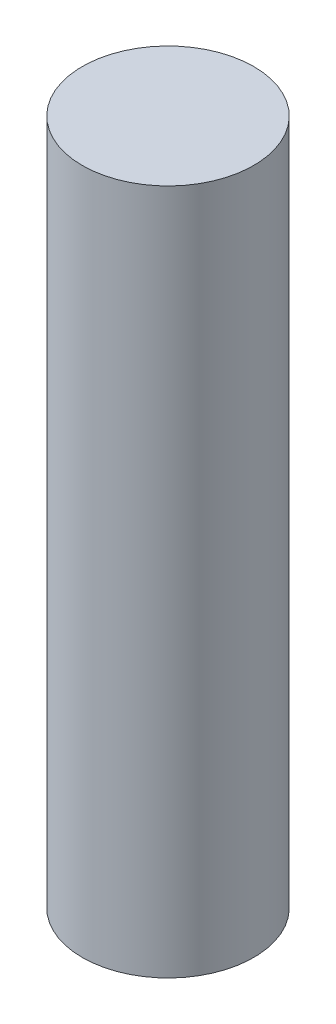
SolidWorks part; units mm, degrees
ref_plane "Front Plane" through (0, 0, 0) normal (0, 0, 1) x (1, 0, 0)
ref_plane "Top Plane" through (0, 0, 0) normal (0, 1, 0) x (1, 0, 0)
ref_plane "Right Plane" through (0, 0, 0) normal (1, 0, 0) x (0, 0, -1)
sketch "Sketch1" plane through (0, 0, 0) normal (0, 1, 0) x (1, 0, 0)
  circle A0 centre (0, 0) radius 10
  dimension "D1" = 20
extrude "Boss-Extrude1" add sketch "Sketch1" along normal blind 80
